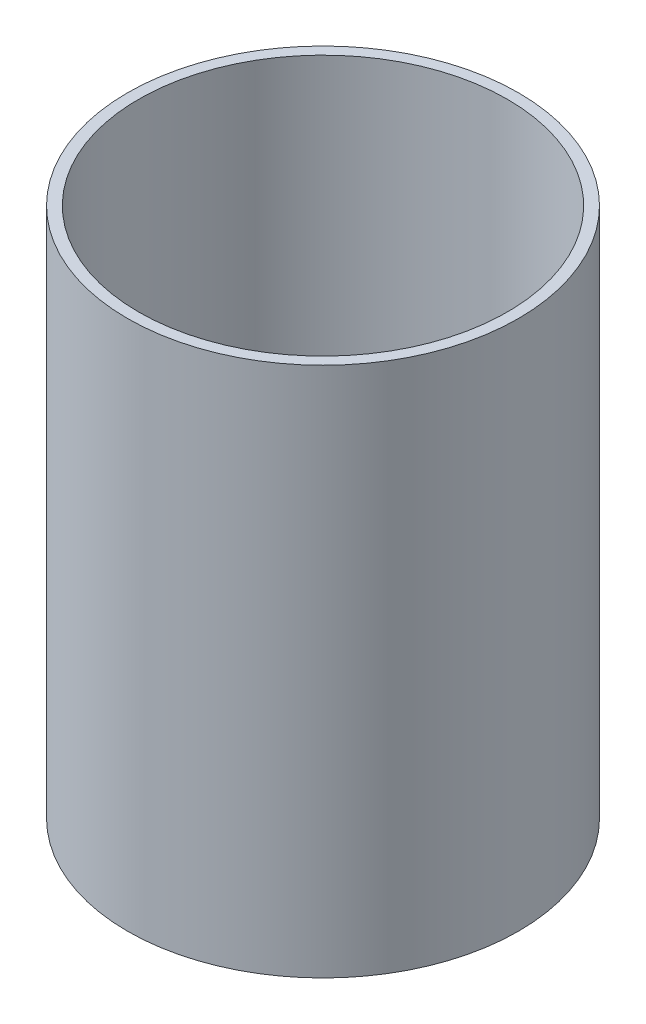
SolidWorks part; units mm, degrees
ref_plane "Alzado" through (0, 0, 0) normal (0, 0, 1) x (1, 0, 0)
ref_plane "Planta" through (0, 0, 0) normal (0, 1, 0) x (1, 0, 0)
ref_plane "Vista lateral" through (0, 0, 0) normal (1, 0, 0) x (0, 0, -1)
sketch "Croquis1" plane through (0, 0, 0) normal (0, 0, 1) x (1, 0, 0)
  line L0 (0, 0) -> (35, 0)
  line L1 (35, 0) -> (35, 95)
  line L2 (0, 25.6165) -> (0, -25.6165) construction
  line L3 (35, 95) -> (33, 95)
  line L4 (33, 95) -> (33, 2)
  line L5 (33, 2) -> (0, 2)
  line L6 (0, 2) -> (0, 0)
  point P7 (0, 0)
  dimension "D1" = 70
  dimension "D2" = 95
  dimension "D3" = 2
  dimension "D4" = 2
revolve "Revolución1" add sketch "Croquis1" angle 360 about L2
